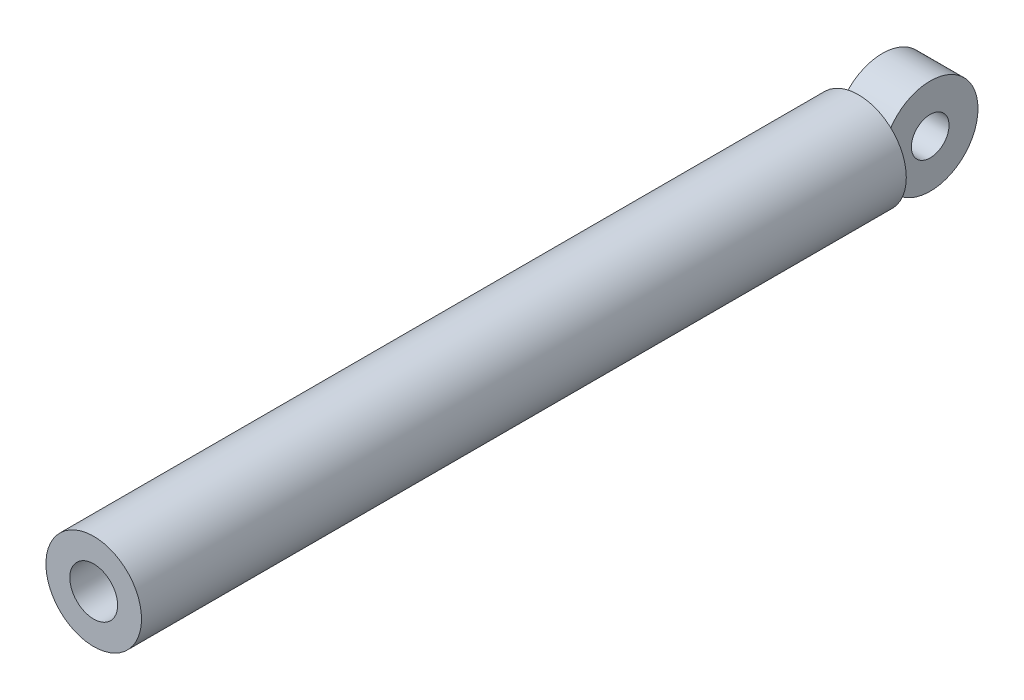
SolidWorks part; units mm, degrees
ref_plane "Front Plane" through (0, 0, 0) normal (0, 0, 1) x (1, 0, 0)
ref_plane "Top Plane" through (0, 0, 0) normal (0, 1, 0) x (1, 0, 0)
ref_plane "Right Plane" through (0, 0, 0) normal (1, 0, 0) x (0, 0, -1)
sketch "Sketch1" plane through (0, 0, 0) normal (0, 0, 1) x (1, 0, 0)
  circle A1 centre (0, 0) radius 6.35
  dimension "D1" = 12.7
extrude "Boss-Extrude1" add sketch "Sketch1" along normal blind 101.6
sketch "Sketch2" plane through (0, 0, 101.6) normal (0, 0, 1) x (1, 0, 0)
  circle A0 centre (0, 0) radius 3.175
  dimension "D1" = 6.35
extrude "Cut-Extrude1" cut sketch "Sketch2" against normal blind 88.9
sketch "Sketch3" plane through (0, 0, 0) normal (1, 0, 0) x (0, 0, -1)
  line L0 (0, -6.35) -> (0, 6.35) construction
  circle A0 centre (6.35, 0) radius 6.35
  circle A1 centre (6.35, 0) radius 2.5
  dimension "D1" = 12.7
  dimension "D2" = 5
extrude "Boss-Extrude2" add sketch "Sketch3" along normal mid plane 6.35 separate body
